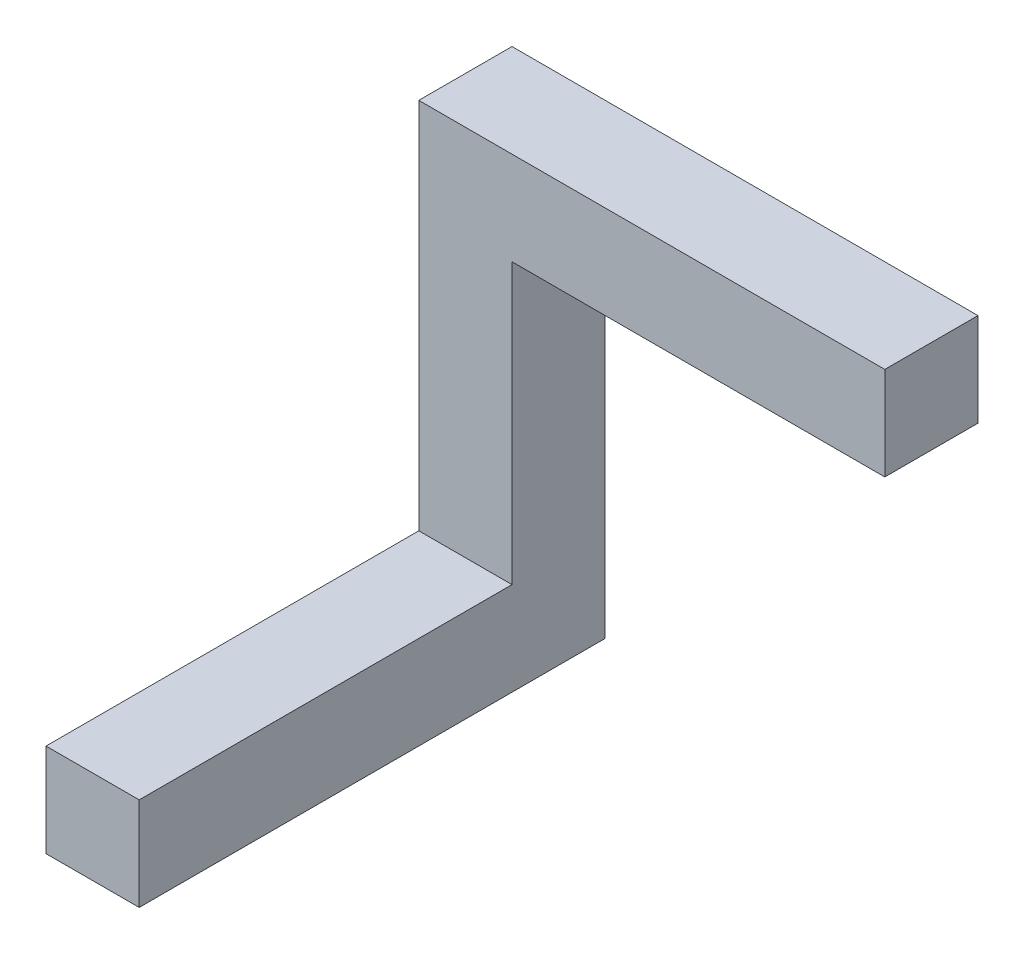
SolidWorks part; units mm, degrees
ref_plane "Alzado" through (0, 0, 0) normal (0, 0, 1) x (1, 0, 0)
ref_plane "Planta" through (0, 0, 0) normal (0, 1, 0) x (1, 0, 0)
ref_plane "Vista lateral" through (0, 0, 0) normal (1, 0, 0) x (0, 0, -1)
sketch "Croquis1" plane through (0, 0, 0) normal (0, 0, 1) x (1, 0, 0)
  line L9 (-130, 135) -> (-130, -15)
  line L10 (-130, 135) -> (20, 135)
  line L12 (-100, 105) -> (20, 105)
  line L13 (20, 135) -> (20, 105)
  line L16 (-130, -15) -> (-100, -15)
  line L17 (-100, 105) -> (-100, -15)
  dimension "D1" = 150
  dimension "D2" = 30
  dimension "D3" = 100
  dimension "D4" = 15
extrude "Saliente-Extruir1" add sketch "Croquis1" along normal blind 30
sketch "Croquis2" plane through (0, 0, 0) normal (0, 0, 1) x (1, 0, 0)
  line L0 (-100, -15) -> (-100, 105) construction
  line L1 (-130, -15) -> (-100, -15)
  line L2 (-130, -15) -> (-130, 15)
  line L3 (-130, 15) -> (-100, 15)
  line L4 (-100, -15) -> (-100, 15)
  dimension "D1" = 30
extrude "Saliente-Extruir3" add sketch "Croquis2" along normal blind 150
